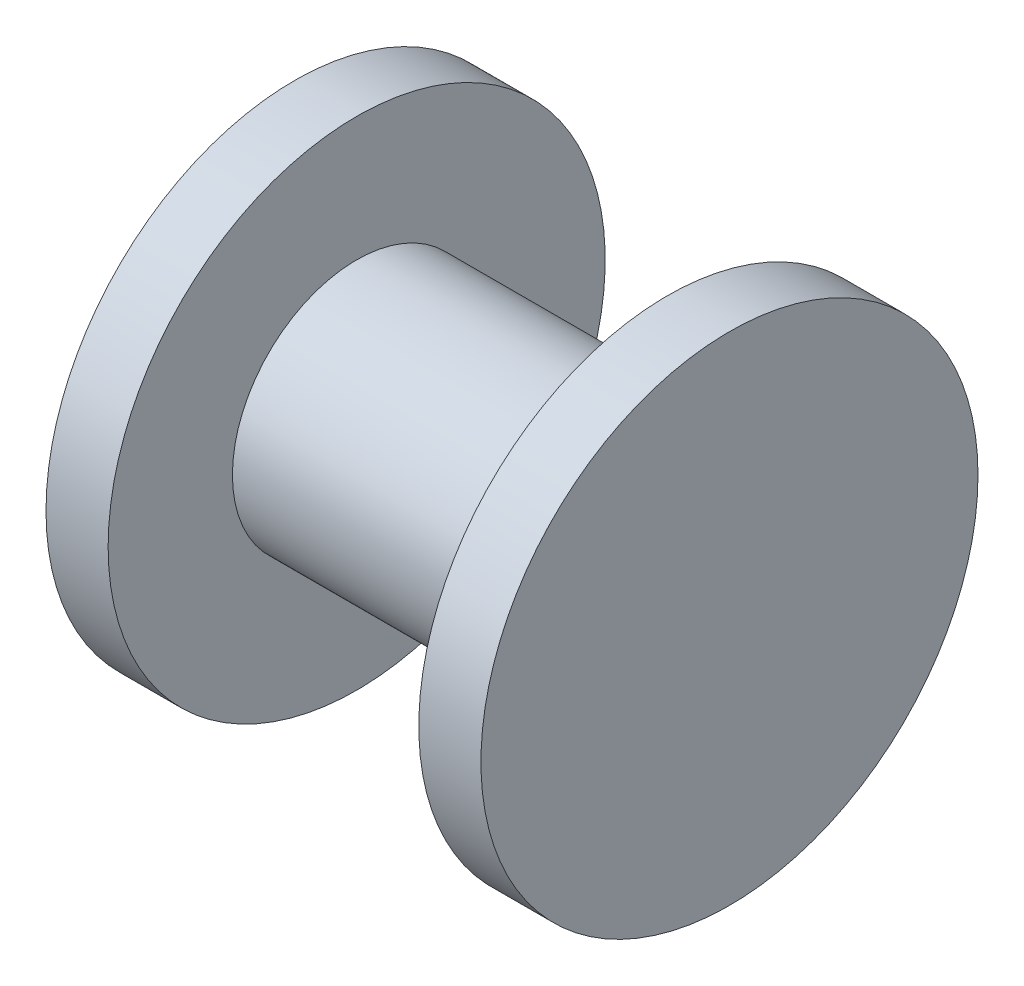
SolidWorks part; units mm, degrees
material "AISI 304"
ref_plane "Front Plane" through (0, 0, 0) normal (0, 0, 1) x (1, 0, 0)
ref_plane "Top Plane" through (0, 0, 0) normal (0, 1, 0) x (1, 0, 0)
ref_plane "Right Plane" through (0, 0, 0) normal (1, 0, 0) x (0, 0, -1)
sketch "Sketch1" plane through (0, 0, 0) normal (0, 0, 1) x (1, 0, 0)
  line L0 (0, 0) -> (0, 16150.6755) construction
  line L1 (0, 0) -> (16150.6755, 0) construction
  line L3 (-12.5, 10) -> (12.5, 10)
  line L4 (-12.5, 10) -> (-12.5, 0)
  line L5 (-12.5, 0) -> (12.5, 0)
  line L6 (12.5, 10) -> (12.5, 0)
  line L7 (-12.5, 10) -> (12.5, 0) construction
  line L8 (-12.5, 0) -> (12.5, 10) construction
  point P5 (0, 5)
  dimension "D1" = 20
  dimension "D2" = 25
revolve "Revolve1" add sketch "Sketch1" angle 360 about L1
sketch "Sketch2" plane through (-12.5, 0, 0) normal (-1, 0, 0) x (0, 0, 1)
  circle A2 centre (0, 0) radius 20
  circle A3 centre (0, 0) radius 20
  dimension "D1" = 10
extrude "Boss-Extrude1" add sketch "Sketch2" along normal blind 5
sketch "Sketch3" plane through (12.5, 0, 0) normal (1, 0, 0) x (0, 0, -1)
  circle A2 centre (0, 0) radius 20
  circle A3 centre (0, 0) radius 20
  dimension "D1" = 10
extrude "Boss-Extrude2" add sketch "Sketch3" along normal blind 5
